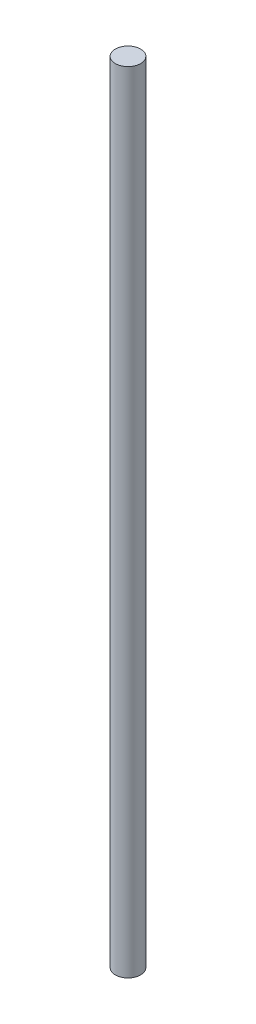
SolidWorks part; units mm, degrees
material "Stainless Steel (ferritic)"
ref_plane "Front Plane" through (0, 0, 0) normal (0, 0, 1) x (1, 0, 0)
ref_plane "Top Plane" through (0, 0, 0) normal (0, 1, 0) x (1, 0, 0)
ref_plane "Right Plane" through (0, 0, 0) normal (1, 0, 0) x (0, 0, -1)
sketch "Sketch1" plane through (0, 0, 0) normal (0, 1, 0) x (1, 0, 0)
  circle A0 centre (0, 0) radius 4
  dimension "D1" = 8
extrude "Boss-Extrude1" add sketch "Sketch1" along normal mid plane 250 contours A0
